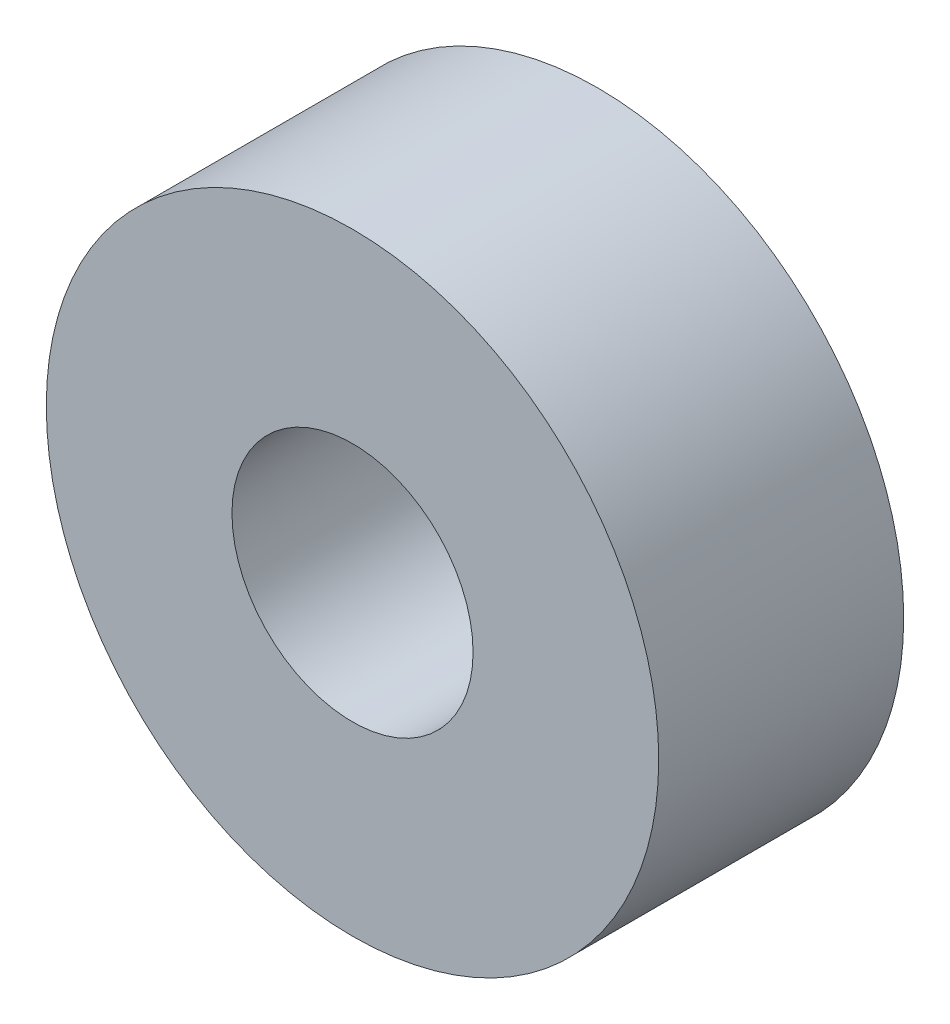
SolidWorks part; units mm, degrees
ref_plane "Front Plane" through (0, 0, 0) normal (0, 0, 1) x (1, 0, 0)
ref_plane "Top Plane" through (0, 0, 0) normal (0, 1, 0) x (1, 0, 0)
ref_plane "Right Plane" through (0, 0, 0) normal (1, 0, 0) x (0, 0, -1)
sketch "Sketch1" plane through (0, 0, 0) normal (0, 0, 1) x (1, 0, 0)
  circle A0 centre (0, 0) radius 12.7
  circle A1 centre (0, 0) radius 5
  dimension "D1" = 25.4
  dimension "D2" = 10
extrude "Boss-Extrude1" add sketch "Sketch1" along normal mid plane 10.16
